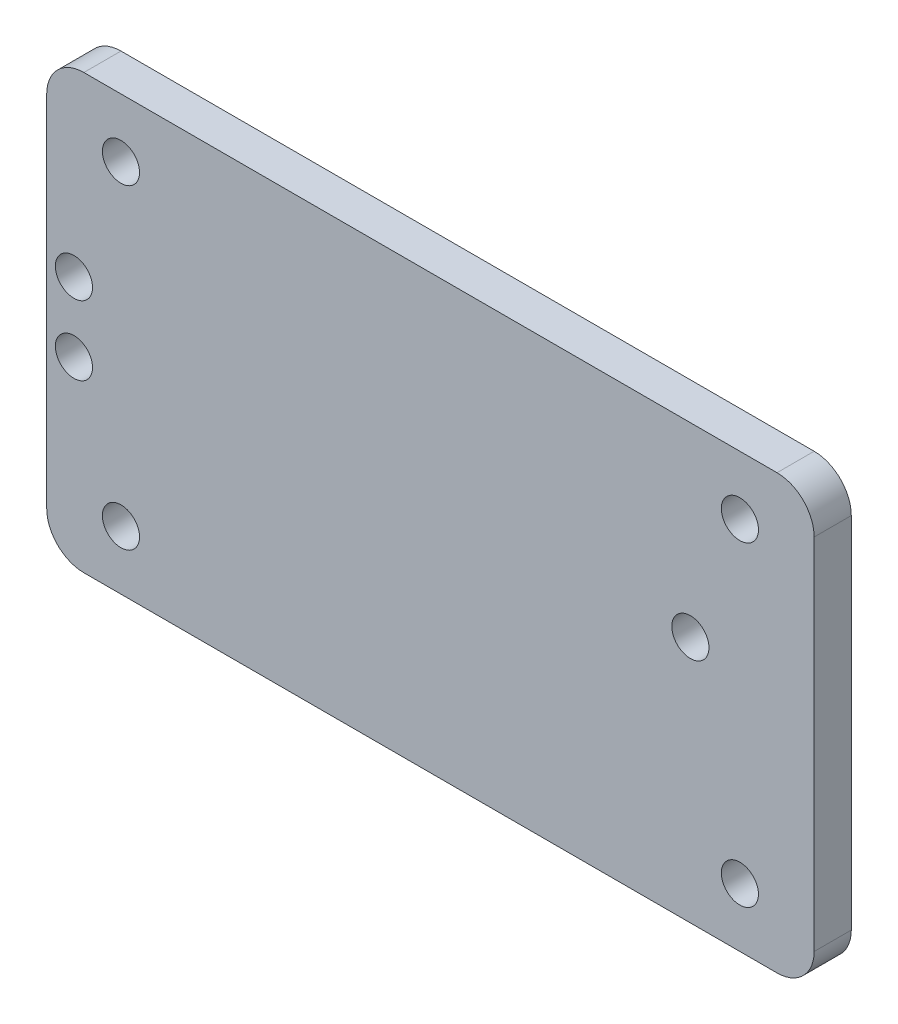
SolidWorks part; units mm, degrees
ref_plane "Front Plane" through (0, 0, 0) normal (0, 0, 1) x (1, 0, 0)
ref_plane "Top Plane" through (0, 0, 0) normal (0, 1, 0) x (1, 0, 0)
ref_plane "Right Plane" through (0, 0, 0) normal (1, 0, 0) x (0, 0, -1)
sketch "Sketch1" plane through (0, 0, 0) normal (0, 0, 1) x (1, 0, 0)
  line L1 (-28, 17.5) -> (28, 17.5)
  line L2 (-31, 14.5) -> (-31, -14.5)
  line L3 (-28, -17.5) -> (28, -17.5)
  line L4 (31, 14.5) -> (31, -14.5)
  line L5 (0, -17.5) -> (0, 17.5) construction
  line L6 (-31, 0) -> (31, 0) construction
  arc A0 (28, -17.5) -> (31, -14.5) centre (28, -14.5) ccw
  arc A1 (-31, -14.5) -> (-28, -17.5) centre (-28, -14.5) ccw
  arc A2 (28, 17.5) -> (31, 14.5) centre (28, 14.5) cw
  arc A3 (-28, 17.5) -> (-31, 14.5) centre (-28, 14.5) ccw
  circle A4 centre (-28.8, 2.8) radius 1.5
  circle A5 centre (-28.8, -2.8) radius 1.5
  circle A6 centre (21, 2.5) radius 1.5
  circle A7 centre (-25, 12.75) radius 1.5
  circle A8 centre (25, 12.75) radius 1.5
  circle A9 centre (25, -12.75) radius 1.5
  circle A10 centre (-25, -12.75) radius 1.5
  point P0 (0, 0)
  point P6 (31, -17.5)
  point P9 (-31, -17.5)
  point P15 (-31, 17.5)
  dimension "D3" = 3
  dimension "D4" = 3
  dimension "D5" = 3
  dimension "D6" = 3
  dimension "D1" = 62
  dimension "D2" = 35
extrude "Boss-Extrude1" add sketch "Sketch1" along normal blind 3
sketch "Sketch2" plane through (0, 0, 3) normal (0, 0, 1) x (1, 0, 0)
  line L0 (-31, 0) -> (31, 0) construction
  line L1 (-31, 14.5) -> (-31, -14.5) construction
  line L2 (31, -14.5) -> (31, 14.5) construction
